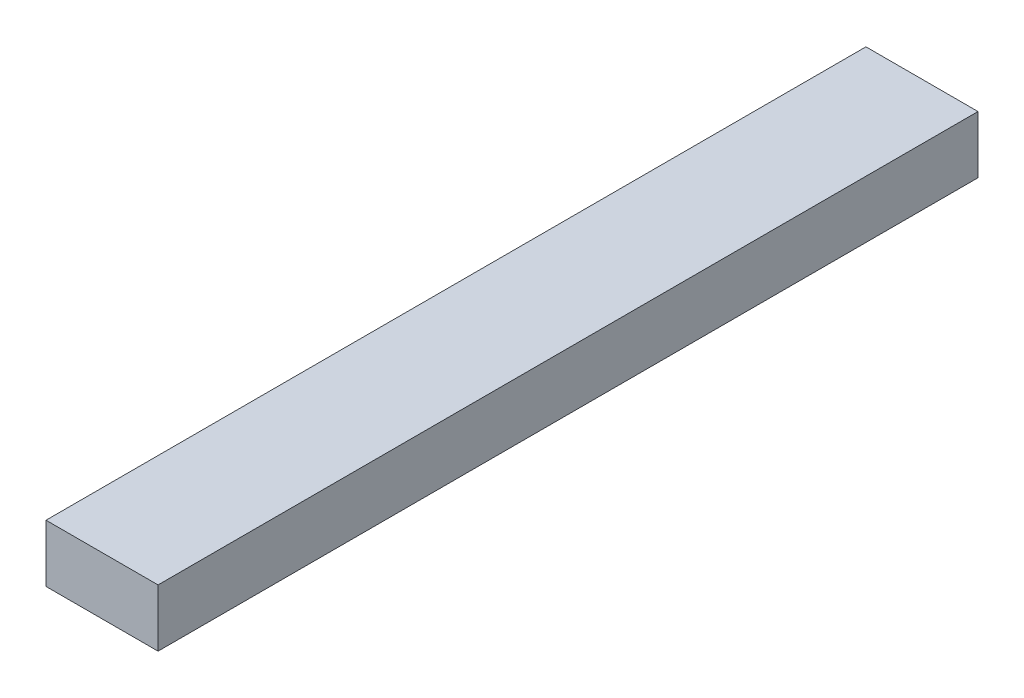
SolidWorks part; units mm, degrees
ref_plane "Front Plane" through (0, 0, 0) normal (0, 0, 1) x (1, 0, 0)
ref_plane "Top Plane" through (0, 0, 0) normal (0, 1, 0) x (1, 0, 0)
ref_plane "Right Plane" through (0, 0, 0) normal (1, 0, 0) x (0, 0, -1)
sketch "Sketch1" plane through (0, 0, 0) normal (0, 0, 1) x (1, 0, 0)
  line L1 (-20.5, 10.5) -> (20.5, 10.5)
  line L2 (-20.5, 10.5) -> (-20.5, -10.5)
  line L3 (-20.5, -10.5) -> (20.5, -10.5)
  line L4 (20.5, 10.5) -> (20.5, -10.5)
  line L5 (-20.5, 10.5) -> (20.5, -10.5) construction
  line L6 (-20.5, -10.5) -> (20.5, 10.5) construction
  point P0 (0, 0)
extrude "Boss-Extrude1" add sketch "Sketch1" along normal blind 300
